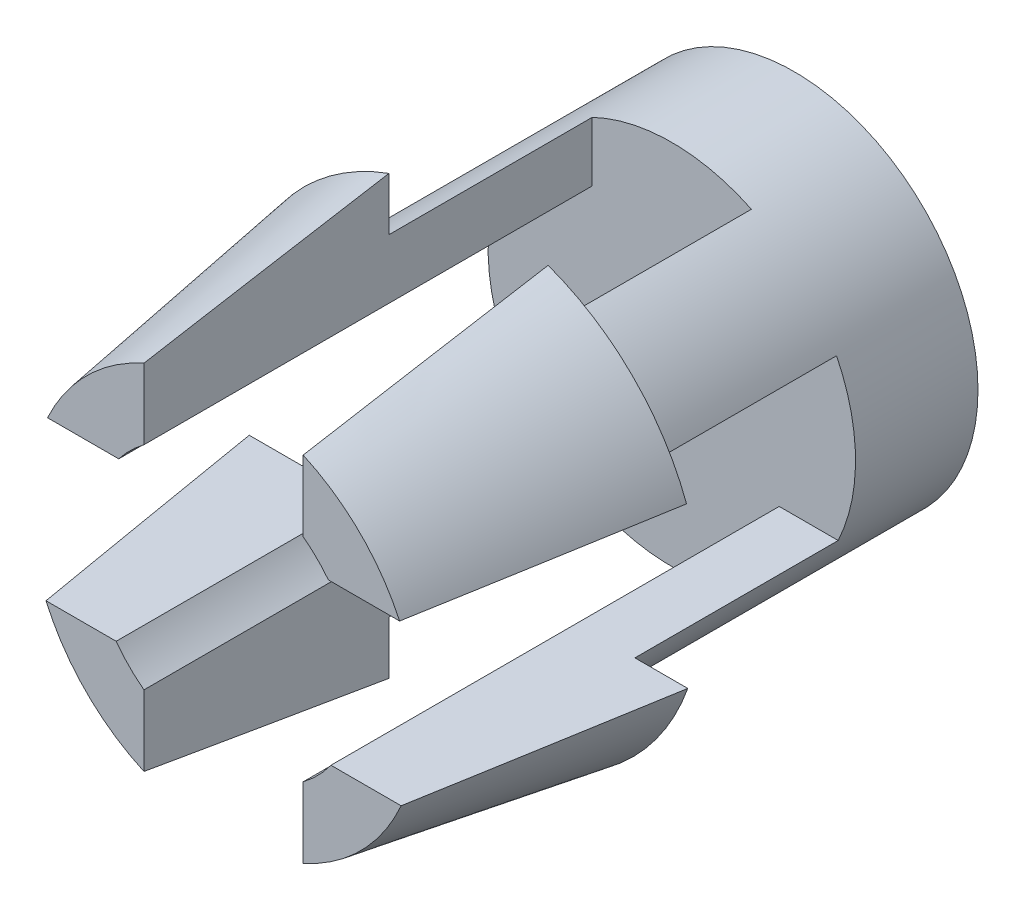
SolidWorks part; units mm, degrees
ref_plane "Front Plane" through (0, 0, 0) normal (0, 0, 1) x (1, 0, 0)
ref_plane "Top Plane" through (0, 0, 0) normal (0, 1, 0) x (1, 0, 0)
ref_plane "Right Plane" through (0, 0, 0) normal (1, 0, 0) x (0, 0, -1)
sketch "Sketch2" plane through (0, 0, 0) normal (0, 0, 1) x (1, 0, 0)
  circle A0 centre (0, 0) radius 1.5
  dimension "D1" = 3
extrude "Boss-Extrude1" add sketch "Sketch2" along normal blind 2.66
sketch "Sketch3" plane through (0, 0, 2.66) normal (0, 0, 1) x (1, 0, 0)
  circle A0 centre (0, 0) radius 1.9
  circle A1 centre (0, 0) radius 1.5 construction
  dimension "D1" = 0.4
extrude "Boss-Extrude2" add sketch "Sketch3" along normal blind 2 draft 9
sketch "Sketch4" plane through (0, 0, 4.66) normal (0, 0, 1) x (1, 0, 0)
  line L6 (-0.65, 2.2213) -> (0.65, 2.2213)
  line L7 (0.65, 2.2213) -> (0.65, 0.8665)
  line L14 (0.856, 0.6638) -> (2.3813, 0.6638)
  line L15 (2.3813, 0.6638) -> (2.3813, -0.6362)
  line L16 (2.3813, -0.6362) -> (0.8767, -0.6362)
  line L17 (0.65, -0.8665) -> (0.65, -2.2213)
  line L18 (0.65, -2.2213) -> (-0.65, -2.2213)
  line L19 (-0.65, -2.2213) -> (-0.65, -0.8665)
  line L20 (-0.8767, -0.6362) -> (-2.3813, -0.6362)
  line L21 (-2.3813, -0.6362) -> (-2.3813, 0.6638)
  line L22 (-2.3813, 0.6638) -> (-0.856, 0.6638)
  line L23 (-0.65, 0.8665) -> (-0.65, 2.2213)
  line L24 (0, 2.2213) -> (0, -2.2213) construction
  line L25 (-2.3813, 0.0138) -> (2.3813, 0.0138) construction
  circle A0 centre (0, 0) radius 1.5832 construction
  arc A1 (-0.8767, -0.6362) -> (-0.65, -0.8665) centre (0, 0) ccw
  arc A2 (0.65, -0.8665) -> (0.8767, -0.6362) centre (0, 0) ccw
  arc A3 (0.856, 0.6638) -> (0.65, 0.8665) centre (0, 0) ccw
  arc A4 (-0.65, 0.8665) -> (-0.856, 0.6638) centre (0, 0) ccw
  point P9 (0, 0)
  point P17 (0, 0)
  point P22 (0, 0)
  dimension "D2" = 0.5
  dimension "D1" = 1.3
extrude "Cut-Extrude1" cut sketch "Sketch4" against normal offset from surface (3.66 mm away) 1 up to face at (1.5, 0, 0)
